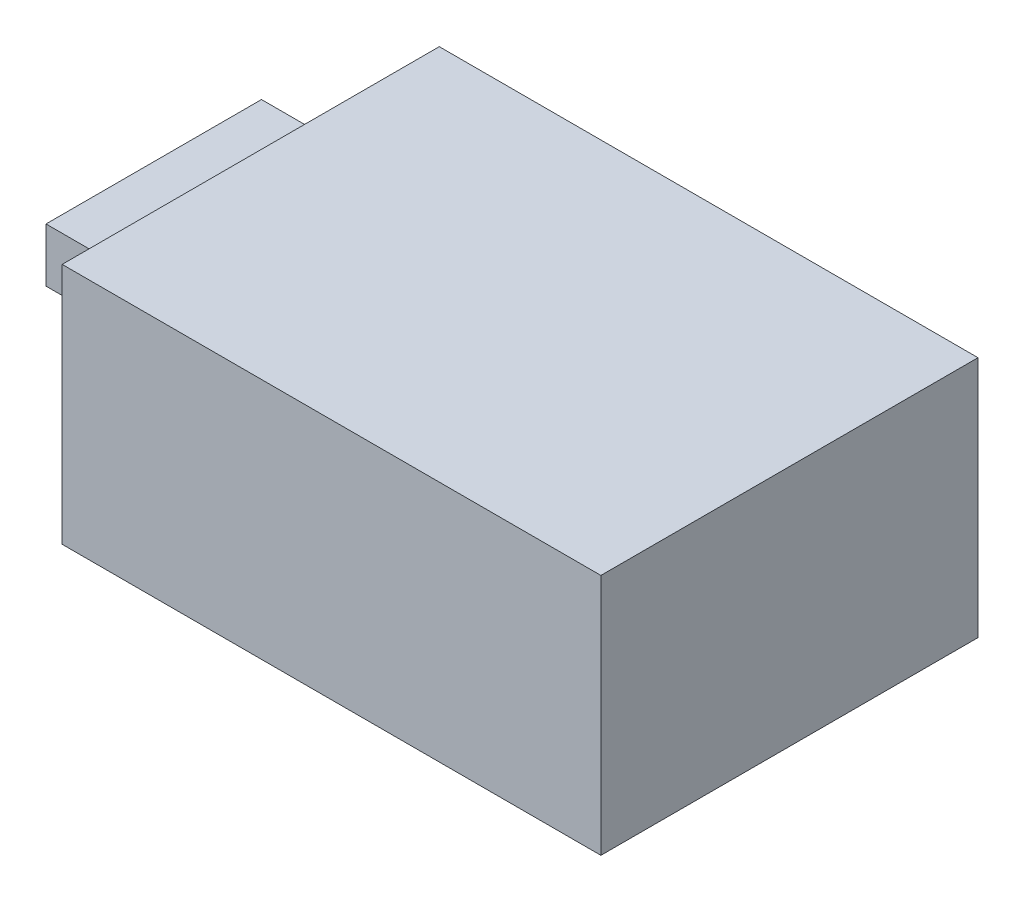
SolidWorks part; units mm, degrees
ref_plane "Plan de face" through (0, 0, 0) normal (0, 0, 1) x (1, 0, 0)
ref_plane "Plan de dessus" through (0, 0, 0) normal (0, 1, 0) x (1, 0, 0)
ref_plane "Plan de droite" through (0, 0, 0) normal (1, 0, 0) x (0, 0, -1)
sketch "Esquisse1" plane through (0, 0, 0) normal (0, 1, 0) x (1, 0, 0)
  line L1 (0, 0) -> (100, 0)
  line L2 (0, 0) -> (0, 70)
  line L3 (0, 70) -> (100, 70)
  line L4 (100, 0) -> (100, 70)
  dimension "D1" = 70
  dimension "D2" = 100
extrude "Boss.-Extru.1" add sketch "Esquisse1" along normal blind 45
sketch "Esquisse2" plane through (0, 0, 0) normal (1, 0, 0) x (0, 0, -1)
  text T1 "Batterie Plomb (AGM) 6 V 1.2 Ah Yuasa NP1.2-6" font "Century Gothic" height 3.5
extrude "Enlèv. mat.-Extru.1" cut sketch "Esquisse2" along normal blind 1
sketch "Esquisse4" plane through (0, 0, 0) normal (-1, 0, 0) x (0, 0, 1)
  line L0 (-70, 0) -> (0, 0) construction
  line L1 (-55, 4) -> (-15, 4)
  line L2 (-55, 4) -> (-55, 14)
  line L3 (-55, 14) -> (-15, 14)
  line L4 (-15, 4) -> (-15, 14)
  line L5 (-7, 33) -> (-47, 33)
  line L6 (-7, 33) -> (-7, 43)
  line L7 (-7, 43) -> (-47, 43)
  line L8 (-47, 33) -> (-47, 43)
  line L9 (0, 45) -> (0, 0) construction
  line L10 (-70, 45) -> (-70, 12.4358) construction
  dimension "D1" = 40
  dimension "D2" = 40
  dimension "D3" = 10
  dimension "D4" = 10
  dimension "D5" = 4
  dimension "D6" = 33
  dimension "D7" = 7
  dimension "D8" = 15
extrude "Boss.-Extru.3" add sketch "Esquisse4" along normal blind 10
